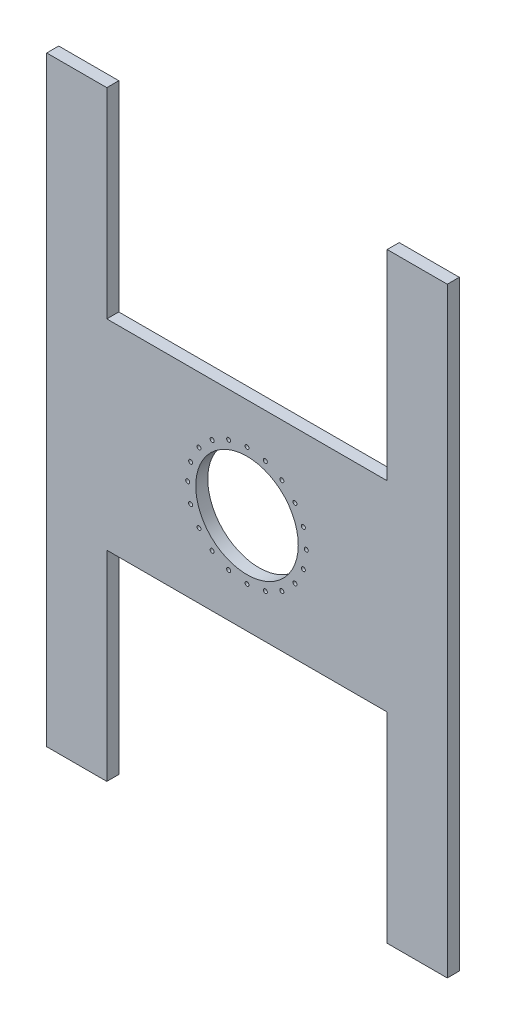
SolidWorks part; units mm, degrees
material "ASTM A36 Acier"
ref_plane "Plan de face" through (0, 0, 0) normal (0, 0, 1) x (1, 0, 0)
ref_plane "Plan de dessus" through (0, 0, 0) normal (0, 1, 0) x (1, 0, 0)
ref_plane "Plan de droite" through (0, 0, 0) normal (1, 0, 0) x (0, 0, -1)
sketch "Esquisse1" plane through (0, 0, 0) normal (0, 0, 1) x (1, 0, 0)
  line L0 (-1000, 2000) -> (-700, 2000)
  line L1 (-700, 2000) -> (-700, 1000)
  line L2 (-700, 1000) -> (700, 1000)
  line L3 (700, 1000) -> (700, 2000)
  line L4 (700, 2000) -> (1000, 2000)
  line L5 (1000, 2000) -> (1000, -1000)
  line L6 (1000, -1000) -> (700, -1000)
  line L7 (700, -1000) -> (700, 0)
  line L8 (700, 0) -> (-700, 0)
  line L9 (-700, 0) -> (-700, -1000)
  line L10 (-700, -1000) -> (-1000, -1000)
  line L11 (-1000, -1000) -> (-1000, 2000)
  point P2 (0, 0)
  point P13 (0, 0)
  point P15 (0, 0)
  dimension "D1" = 2000
  dimension "D2" = 3000
  dimension "D3" = 3000
  dimension "D4" = 300
  dimension "D5" = 300
  dimension "D6" = 300
  dimension "D7" = 300
  dimension "D8" = 1000
  dimension "D9" = 1000
  dimension "D10" = 1400
extrude "Boss.-Extru.1" add sketch "Esquisse1" along normal blind 60
sketch "Esquisse2" plane through (0, 0, 60) normal (0, 0, 1) x (1, 0, 0)
  circle A0 centre (0, 500) radius 256
  dimension "D1" = 512
  dimension "D2" = 500
extrude "Enlèv. mat.-Extru.1" cut sketch "Esquisse2" against normal through all
sketch "Esquisse4" plane through (0, 0, 0) normal (1, 0, 0) x (0, 0, -1)
  line L0 (0, 500) -> (1429.3387, 500) construction
  dimension "D1" = 500
sketch "Esquisse5" plane through (0, 0, 0) normal (0, 0, 1) x (1, 0, 0)
  circle A0 centre (0, 796) radius 10
  dimension "D1" = 20
  dimension "D2" = 296
extrude "Enlèv. mat.-Extru.3" cut sketch "Esquisse5" along normal through all
pattern_circular "Répétition circulaire1" count 20 every 18 about axis through (0, 500, 0) along (0, 0, 1) of "Enlèv. mat.-Extru.3"
